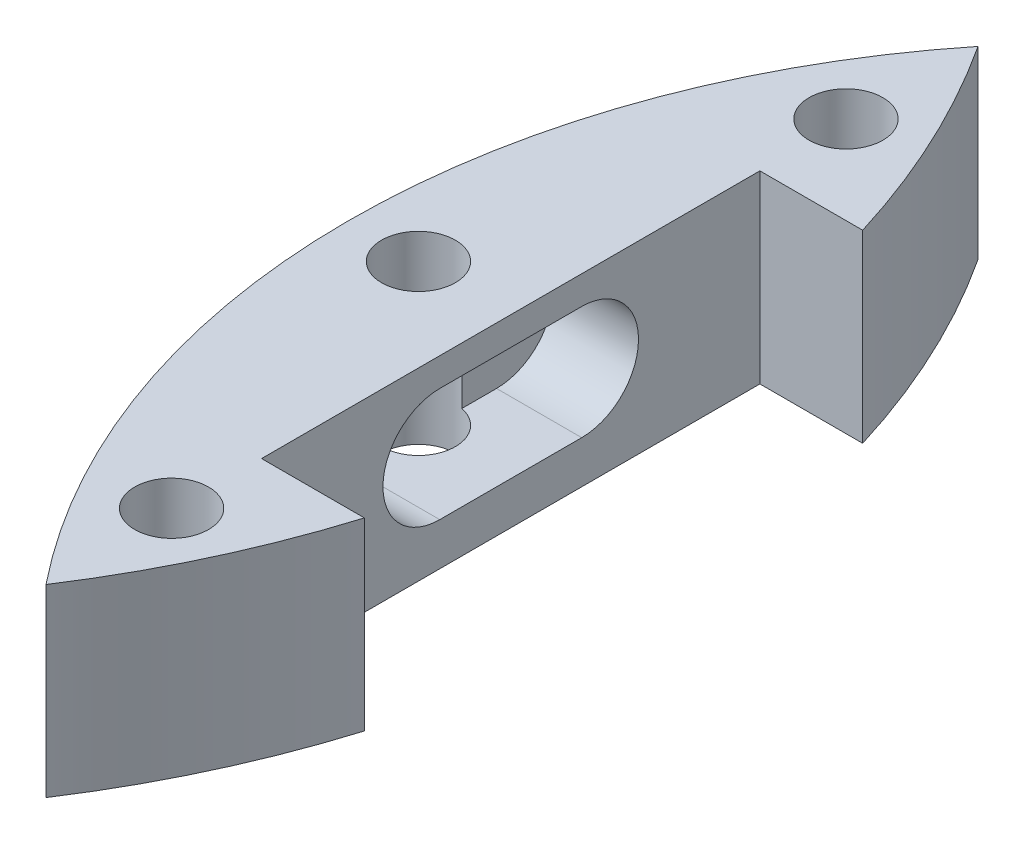
SolidWorks part; units mm, degrees
ref_plane "前视基准面" through (0, 0, 0) normal (0, 0, 1) x (1, 0, 0)
ref_plane "上视基准面" through (0, 0, 0) normal (0, 1, 0) x (1, 0, 0)
ref_plane "右视基准面" through (0, 0, 0) normal (1, 0, 0) x (0, 0, -1)
sketch "草图1" plane through (0, 0, 0) normal (0, 1, 0) x (1, 0, 0)
  line L0 (-41.1362, -23.75) -> (-41.1362, 23.75)
  line L1 (41, 17.55) -> (-41, 17.55)
  line L2 (41, 17.55) -> (41, -17.55)
  line L3 (41, -17.55) -> (-41, -17.55)
  line L4 (-41, 17.55) -> (-41, -17.55)
  line L5 (41, 17.55) -> (-41, -17.55) construction
  line L6 (41, -17.55) -> (-41, 17.55) construction
  line L7 (-41.1362, 23.75) -> (0, 0)
  line L8 (0, 0) -> (-41.1362, -23.75)
  line L9 (-41.1362, 0) -> (-91.1362, 0)
  circle A0 centre (0, 0) radius 52.45
  circle A1 centre (0, 0) radius 47.5
  circle A2 centre (-41.1362, -23.75) radius 2.6
  circle A3 centre (-41.1362, 23.75) radius 2.6
  circle A4 centre (-91.1362, 0) radius 60
  circle A5 centre (-47.5, 0) radius 2.6
  dimension "D1" = 104.9
  dimension "D4" = 95
  dimension "D7" = 5.2
  dimension "D8" = 5.2
  dimension "D11" = 120
  dimension "D12" = 5.2
  dimension "D2" = 35.1
  dimension "D3" = 41
  dimension "D5" = 60
  dimension "D6" = 90
  dimension "D9" = 50
  dimension "D10" = 0
extrude "凸台-拉伸1" add sketch "草图1" along normal blind 13 contours A5 L9 A0 A4 A1 A2 | A1 A4 L3 L8 A2 | A3 L0 A2 L8 L3 L4 L1 L7 | A5 A1 A2 L0 L9 | A5 L9 L0 A3 A1 | A5 A1 A3 A4 A0 L9 | L1 A4 A1 A3 L7
sketch "草图2" plane through (0, 0, 0) normal (0, -1, 0) x (-1, 0, 0)
sketch "草图3" plane through (-41, 0, 0) normal (1, 0, 0) x (0, 0, -1)
  line L0 (-5, 7) -> (5, 7) construction
  line L1 (-5, 11) -> (5, 11)
  line L2 (-5, 3) -> (5, 3)
  line L3 (17.55, 0) -> (-17.55, 0) construction
  arc A0 (-5, 11) -> (-5, 3) centre (-5, 7) ccw
  arc A1 (5, 3) -> (5, 11) centre (5, 7) ccw
  point P2 (0, 7)
  dimension "D1" = 4
  dimension "D2" = 7
  dimension "D3" = 10
  dimension "D4" = 0
extrude "切除-拉伸1" cut sketch "草图3" against normal blind 6
